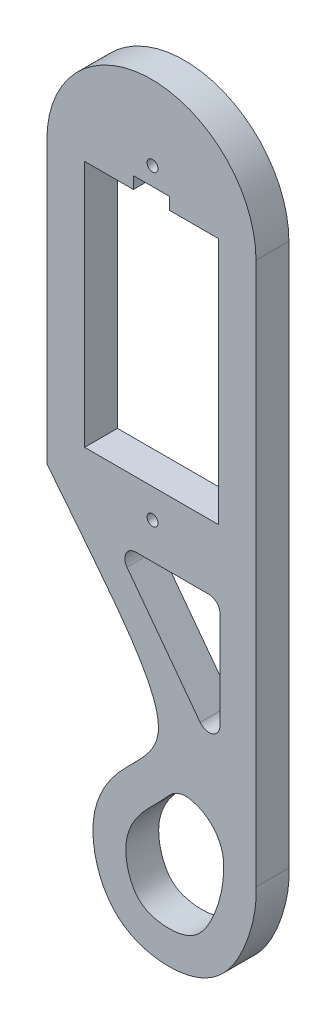
SolidWorks part; units mm, degrees
ref_plane "Ebene vorne" through (0, 0, 0) normal (0, 0, 1) x (1, 0, 0)
ref_plane "Ebene oben" through (0, 0, 0) normal (0, 1, 0) x (1, 0, 0)
ref_plane "Ebene rechts" through (0, 0, 0) normal (1, 0, 0) x (0, 0, -1)
sketch "Skizze1" plane through (0, 0, 0) normal (0, 0, 1) x (1, 0, 0)
  line L0 (-126.0223, 119.1663) -> (-122.0223, 119.1663)
  line L4 (-133.5624, 119.1663) -> (-133.5624, 93.5473)
  line L5 (-114.4822, 69.6447) -> (-114.4822, 119.1663)
  line L9 (-130.1223, 96.5663) -> (-117.9223, 96.5663)
  line L10 (-117.9223, 119.1663) -> (-117.9223, 96.5663)
  line L11 (-122.0223, 119.1663) -> (-117.9223, 119.1663)
  line L12 (-130.1223, 119.1663) -> (-126.0223, 119.1663)
  line L13 (-130.1223, 119.1663) -> (-130.1223, 96.5663)
  line L17 (-125.4512, 90.6233) -> (-118.7774, 90.6233)
  line L18 (-117.7774, 89.6233) -> (-117.7774, 80.7031)
  line L19 (-119.5781, 80.104) -> (-126.2519, 89.0243)
  arc A2 (-114.4822, 119.1663) -> (-133.5624, 119.1663) centre (-124.0223, 119.1663) ccw
  arc A7 (-117.7774, 89.6233) -> (-118.7774, 90.6233) centre (-118.7774, 89.6233) ccw
  arc A8 (-119.5781, 80.104) -> (-117.7774, 80.7031) centre (-118.7774, 80.7031) ccw
  arc A9 (-125.4512, 90.6233) -> (-126.2519, 89.0243) centre (-125.4512, 89.6233) ccw
  spline S2 degree 3 poles (-133.5624, 93.5473) (-128.0138, 86.4433) (-120.198, 77.816) (-127.4695, 72.7523) (-130.1691, 67.2248) (-128.0406, 60.4758) (-122.1694, 58.8004) (-116.1918, 60.8742) (-114.3118, 67.5275) (-114.4822, 69.6447) knots 0 0 0 0 0.225721 0.353252 0.479385 0.607669 0.727502 0.851807 1 1 1 1
  dimension "D1" = 12.2
  dimension "D2" = 22.6
  dimension "D4" = 3.4401
extrude "Aufsatz-Linear austragen1" add sketch "Skizze1" against normal blind 3
hole_wizard "Ø1.0 (1) Durchmesser Bohrung1" positions "Skizze2" profile "Skizze3" hole size "Ø1.0" standard "DIN"
sketch "Skizze2" plane through (0, 0, 0) normal (0, 0, 1) x (1, 0, 0)
  point P0 (-123.9223, 121.9163)
  point P2 (-123.9223, 93.9163)
sketch "Skizze3" plane through (-123.9223, 121.9163, 0) normal (1, 0, 0) x (0, -1, 0)
  line L0 (0, 0) -> (0, 8.3004)
  line L1 (0, 8.3004) -> (0.5, 8)
  line L2 (0.5, 8) -> (0.5, 0)
  line L5 (0.5, 0) -> (0, 0)
  line L10 (0, 8.3004) -> (-0.5, 8) construction
  line L11 (0, -6.35) -> (0, 107.95) construction
  dimension "Bohrerdurchmesser" = 1
  dimension "Bohrungstiefe" = 8
  dimension "Spitzenwinkel" = 118
sketch "Skizze4" plane through (0, 0, 0) normal (0, 0, 1) x (1, 0, 0)
  arc A0 (-117.4725, 69.4041) -> (-120.5952, 73.5891) centre (-121.1441, 69.9219) ccw
  arc A1 (-122.4073, 72.9156) -> (-120.5952, 73.5891) centre (-120.8913, 71.6111) cw
  spline S2 degree 3 poles (2808.058, 634.3742) (-351.9716, 316.9855) (-172.3143, 147.6883) (-126.1418, 89.0069) (-125.4881, 88.1628) (-124.2633, 86.5189) (-123.6921, 85.7194) (-122.653, 84.1506) (-122.1848, 83.3817) (-121.3763, 81.841) (-121.0341, 81.0692) (-120.6579, 79.8584) (-120.5558, 79.4455) (-120.4154, 78.5931) (-120.3773, 78.153) (-120.3879, 77.4751) (-120.403, 77.2452) (-120.4586, 76.7873) (-120.4985, 76.563) (-120.6496, 75.9098) (-120.7921, 75.5014) (-121.1264, 74.7508) (-121.3177, 74.408) (-121.7205, 73.78) (-121.932, 73.4943) (-122.5712, 72.7018) (-123.0025, 72.2568) (-123.7988, 71.4556) (-124.1647, 71.0994) (-124.6189, 70.619) (-124.7512, 70.472) (-125.0008, 70.1753) (-125.1176, 70.0266) (-125.4432, 69.5809) (-125.6275, 69.2841) (-125.9327, 68.6939) (-126.0537, 68.4006) (-126.2373, 67.8116) (-126.3002, 67.5159) (-126.3517, 67.0585) (-126.3616, 66.9045) (-126.3665, 66.5838) (-126.3613, 66.4176) (-126.3218, 65.9109) (-126.2633, 65.5627) (-126.0882, 64.8942) (-125.9716, 64.5741) (-125.7014, 64.0062) (-125.5478, 63.7588) (-125.3167, 63.4638) (-125.241, 63.3793) (-125.0885, 63.2294) (-125.007, 63.1592) (-124.7424, 62.9601) (-124.5386, 62.842) (-124.0698, 62.6404) (-123.8049, 62.5576) (-123.2293, 62.4396) (-122.919, 62.4047) (-122.4401, 62.3921) (-122.2767, 62.3946) (-121.9622, 62.4122) (-121.8099, 62.4274) (-121.3699, 62.4916) (-121.0996, 62.5588) (-120.6008, 62.7401) (-120.372, 62.8536) (-119.934, 63.1416) (-119.7239, 63.3163) (-119.4099, 63.6563) (-119.3066, 63.7815) (-119.0887, 64.0801) (-118.9766, 64.2507) (-118.6442, 64.8121) (-118.4289, 65.2523) (-118.0526, 66.1841) (-117.8909, 66.6759) (-117.6419, 67.6283) (-117.5547, 68.0898) (-117.4843, 68.6845) (-117.4709, 68.8662) (-117.1747, 78.2998) (-147.9029, -0.9669) (873.4477, -2761.5244) knots -2.016215 -2.016215 -2.016215 -2.016215 0.0625 0.0625 0.09375 0.09375 0.125 0.125 0.15625 0.15625 0.1875 0.1875 0.203125 0.203125 0.21875 0.21875 0.226563 0.226563 0.234375 0.234375 0.25 0.25 0.265625 0.265625 0.28125 0.28125 0.3125 0.3125 0.34375 0.34375 0.359375 0.359375 0.375 0.375 0.40625 0.40625 0.4375 0.4375 0.46875 0.46875 0.484375 0.484375 0.5 0.5 0.53125 0.53125 0.5625 0.5625 0.59375 0.59375 0.609375 0.609375 0.625 0.625 0.65625 0.65625 0.6875 0.6875 0.71875 0.71875 0.734375 0.734375 0.75 0.75 0.78125 0.78125 0.8125 0.8125 0.84375 0.84375 0.859375 0.859375 0.875 0.875 0.90625 0.90625 0.9375 0.9375 0.96875 0.96875 0.984375 0.984375 1.910878 1.910878 1.910878 1.910878 only from (-131.1981, 95.394) to (-117.4725, 69.4041)
  spline S3 degree 3 poles (-122.4073, 72.9156) (-122.7465, 72.5213) (-123.0841, 72.1748) (-123.7988, 71.4556) (-124.1647, 71.0994) (-124.6189, 70.619) (-124.7512, 70.472) (-125.0008, 70.1753) (-125.1176, 70.0266) (-125.4432, 69.5809) (-125.6275, 69.2841) (-125.9327, 68.6939) (-126.0537, 68.4006) (-126.2373, 67.8116) (-126.3002, 67.5159) (-126.3517, 67.0585) (-126.3616, 66.9045) (-126.3665, 66.5838) (-126.3613, 66.4176) (-126.3218, 65.9109) (-126.2633, 65.5627) (-126.0882, 64.8942) (-125.9716, 64.5741) (-125.7014, 64.0062) (-125.5478, 63.7588) (-125.3167, 63.4638) (-125.241, 63.3793) (-125.0885, 63.2294) (-125.007, 63.1592) (-124.7424, 62.9601) (-124.5386, 62.842) (-124.0698, 62.6404) (-123.8049, 62.5576) (-123.2293, 62.4396) (-122.919, 62.4047) (-122.4401, 62.3921) (-122.2767, 62.3946) (-121.9622, 62.4122) (-121.8099, 62.4274) (-121.3699, 62.4916) (-121.0996, 62.5588) (-120.6008, 62.7401) (-120.372, 62.8536) (-119.934, 63.1416) (-119.7239, 63.3163) (-119.4099, 63.6563) (-119.3066, 63.7815) (-119.0887, 64.0801) (-118.9766, 64.2507) (-118.6442, 64.8121) (-118.4289, 65.2523) (-118.0526, 66.1841) (-117.8909, 66.6759) (-117.6419, 67.6283) (-117.5547, 68.0898) (-117.4843, 68.6845) (-117.4709, 68.8662) (-117.461, 69.1791) (-117.4649, 69.3104) (-117.4725, 69.4041) knots 0.287652 0.287652 0.287652 0.287652 0.3125 0.3125 0.34375 0.34375 0.359375 0.359375 0.375 0.375 0.40625 0.40625 0.4375 0.4375 0.46875 0.46875 0.484375 0.484375 0.5 0.5 0.53125 0.53125 0.5625 0.5625 0.59375 0.59375 0.609375 0.609375 0.625 0.625 0.65625 0.65625 0.6875 0.6875 0.71875 0.71875 0.734375 0.734375 0.75 0.75 0.78125 0.78125 0.8125 0.8125 0.84375 0.84375 0.859375 0.859375 0.875 0.875 0.90625 0.90625 0.9375 0.9375 0.96875 0.96875 0.984375 0.984375 1 1 1 1
  dimension "D2" = 2
  dimension "D1" = 3
extrude "Schnitt-Linear austragen1" cut sketch "Skizze4" against normal blind 10
sketch "Skizze5" plane through (0, 0, 0) normal (0, 0, 1) x (1, 0, 0)
  line L0 (-117.9223, 119.1663) -> (-130.1223, 119.1663) construction
  line L1 (-125.6723, 119.1663) -> (-122.3723, 119.1663)
  line L2 (-125.6723, 119.1663) -> (-125.6723, 120.2663)
  line L3 (-125.6723, 120.2663) -> (-122.3723, 120.2663)
  line L4 (-122.3723, 119.1663) -> (-122.3723, 120.2663)
  point P6 (-124.0223, 119.1663)
  point P7 (-124.0223, 119.1663)
  dimension "D1" = 1.1
  dimension "D2" = 3.3
extrude "Schnitt-Linear austragen2" cut sketch "Skizze5" against normal blind 10
